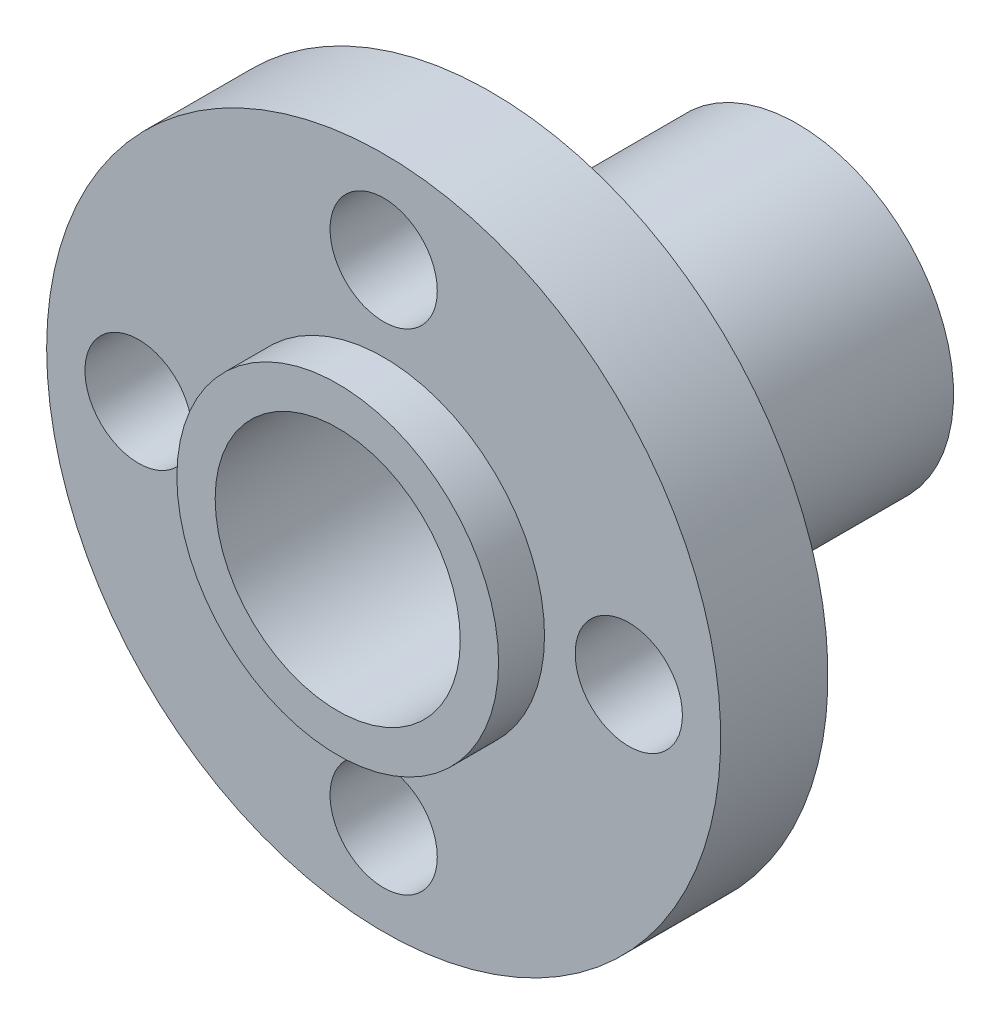
SolidWorks part; units mm, degrees
ref_plane "Front Plane" through (0, 0, 0) normal (0, 0, 1) x (1, 0, 0)
ref_plane "Top Plane" through (0, 0, 0) normal (0, 1, 0) x (1, 0, 0)
ref_plane "Right Plane" through (0, 0, 0) normal (1, 0, 0) x (0, 0, -1)
sketch "Sketch1" plane through (0, 0, 0) normal (0, 0, 1) x (1, 0, 0)
  circle A0 centre (0, 0) radius 5.25
  dimension "D1" = 10.5
extrude "Boss-Extrude1" add sketch "Sketch1" against normal blind 1.5
sketch "Sketch2" plane through (0, 0, -1.5) normal (0, 0, -1) x (-1, 0, 0)
  circle A0 centre (0, 0) radius 11
  dimension "D1" = 22
extrude "Boss-Extrude2" add sketch "Sketch2" along normal blind 3.5
sketch "Sketch3" plane through (0, 0, -5) normal (0, 0, -1) x (-1, 0, 0)
  circle A0 centre (0, 0) radius 5.1
  dimension "D1" = 10.2
extrude "Boss-Extrude3" add sketch "Sketch3" along normal blind 10
sketch "Sketch4" plane through (0, 0, -15) normal (0, 0, -1) x (-1, 0, 0)
  circle A0 centre (0, 0) radius 4
  dimension "D1" = 8
extrude "Cut-Extrude1" cut sketch "Sketch4" against normal through all
sketch "Sketch5" plane through (0, 0, -1.5) normal (0, 0, 1) x (1, 0, 0)
  circle A0 centre (-8, 0) radius 1.75
  circle A1 centre (0, 8) radius 1.75
  circle A2 centre (8, 0) radius 1.75
  circle A3 centre (0, -8) radius 1.75
  point P12 (0, 0)
  dimension "D1" = 3.5
  dimension "D2" = 4
extrude "Cut-Extrude2" cut sketch "Sketch5" against normal blind 10
